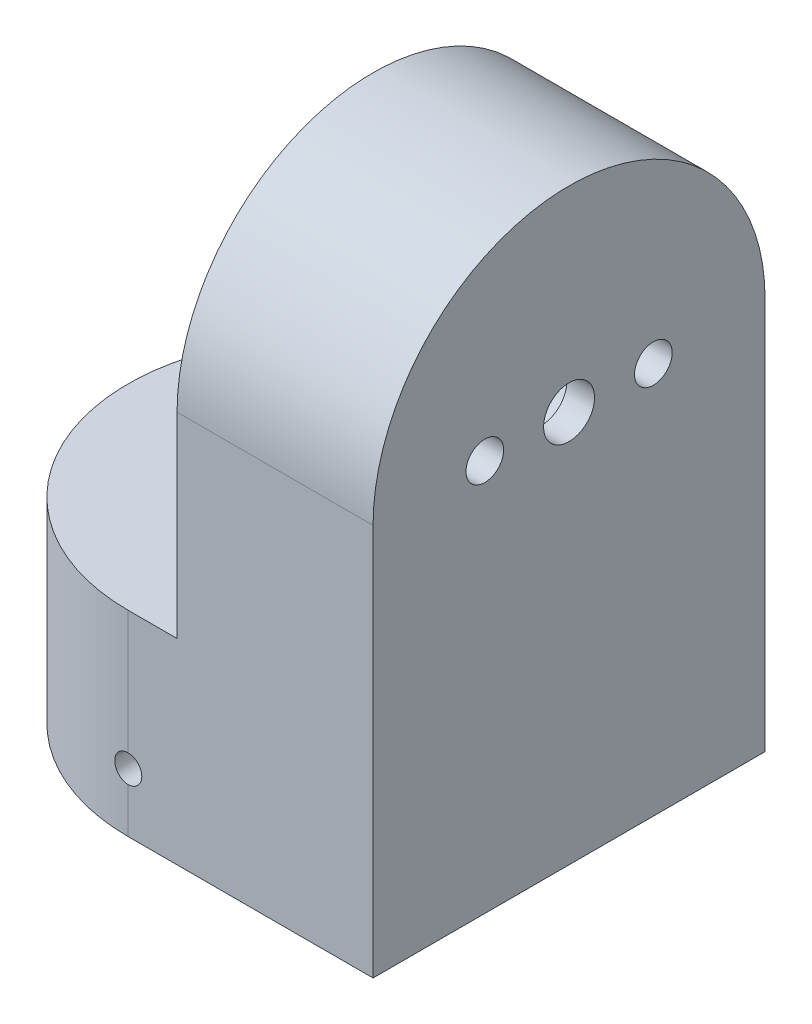
SolidWorks part; units mm, degrees
ref_plane "Front Plane" through (0, 0, 0) normal (0, 0, 1) x (1, 0, 0)
ref_plane "Top Plane" through (0, 0, 0) normal (0, 1, 0) x (1, 0, 0)
ref_plane "Right Plane" through (0, 0, 0) normal (1, 0, 0) x (0, 0, -1)
sketch "Sketch1" plane through (0, 0, 0) normal (0, 1, 0) x (1, 0, 0)
  circle A0 centre (0, 0) radius 12.7
  dimension "D1" = 25.4
extrude "Boss-Extrude1" add sketch "Sketch1" along normal blind 12.7
sketch "Sketch2" plane through (0, 0, 0) normal (0, -1, 0) x (1, 0, 0)
  circle A0 centre (0, 0) radius 1.6256
  dimension "D1" = 3.2512
extrude "Cut-Extrude1" cut sketch "Sketch2" against normal blind 9.525
sketch "Sketch3" plane through (0, 0, 0) normal (0, -1, 0) x (1, 0, 0)
  circle A0 centre (0, 0) radius 9.525
  dimension "D1" = 19.05
extrude "Cut-Extrude2" cut sketch "Sketch3" against normal blind 2.54 contours A0
sketch "Sketch14" plane through (0, 12.7, 0) normal (0, 1, 0) x (1, 0, 0)
  line L0 (0, 12.7) -> (15.875, 12.7)
  line L1 (15.875, 12.7) -> (15.875, -12.7)
  line L2 (15.875, -12.7) -> (0, -12.7)
  circle A0 centre (0, 0) radius 12.7
  circle M3 centre (0, 0) radius 12.7
  dimension "D1" = 25.4
  dimension "D2" = 15.875
extrude "Boss-Extrude6" add sketch "Sketch14" against normal up to surface (12.7 mm away) contours L2 L1 L0 M3 up to face at (0, 0, -9.525)
hole_wizard "#2-56 Tapped Hole1" positions "Sketch6" profile "Sketch5" tap size "#2-56" standard "ANSI Inch"
sketch "Sketch6" plane through (0, 0, 0) normal (0, 0, 1) x (1, 0, 0)
  line L1 (-1.6256, 2.54) -> (1.6256, 2.54) construction
  point P0 (0, 3.81)
  dimension "D1" = 1.27
sketch "Sketch5" plane through (0, 3.81, 0) normal (1, 0, 0) x (0, 1, 0)
  line L0 (0, 0) -> (0, 13.7422)
  line L1 (0, 13.7422) -> (0.889, 13.208)
  line L2 (0.889, 13.208) -> (0.889, 0)
  line L5 (0.889, 0) -> (0, 0)
  line L10 (0, 13.7422) -> (-0.889, 13.208) construction
  line L11 (0, -6.35) -> (0, 107.95) construction
  dimension "Tap Drill Dia." = 1.778
  dimension "Tap Drill Depth" = 13.208
  dimension "Drill Angle" = 118
sketch "Sketch15" plane through (15.875, 0, 0) normal (1, 0, 0) x (0, 0, -1)
  line L1 (12.7, 12.7) -> (-12.7, 12.7) construction
  line L2 (-12.7, 25.4) -> (-12.7, 12.7)
  line L3 (-12.7, 12.7) -> (12.7, 12.7)
  line L4 (12.7, 12.7) -> (12.7, 25.4)
  circle A0 centre (0, 25.4) radius 12.7
  line M4 (12.7, 12.7) -> (-12.7, 12.7)
  dimension "D1" = 25.4
  dimension "D2" = 12.7
  dimension "D3" = 0
extrude "Boss-Extrude8" add sketch "Sketch15" against normal blind 12.7 contours A0 | A0 L2 L3 | A0 L4 M4
sketch "Sketch17" plane through (3.175, 0, 0) normal (-1, 0, 0) x (0, 0, 1)
  line L0 (-12.7, 25.4) -> (12.7, 25.4) construction
  line L1 (0, 38.1) -> (0, 12.7) construction
  line L2 (-12.7, 12.7) -> (12.7, 12.7) construction
  arc A0 (12.7, 25.4) -> (-12.7, 25.4) centre (0, 25.4) ccw construction
  circle A1 centre (0, 25.4) radius 1.651
  dimension "D1" = 3.302
extrude "Cut-Extrude4" cut sketch "Sketch17" against normal up to surface (12.7 mm away) up to face at (15.875, 15.875, 0)
sketch "Sketch18" plane through (3.175, 0, 0) normal (-1, 0, 0) x (0, 0, 1)
  circle A0 centre (0, 25.4) radius 3.81
  dimension "D1" = 7.62
extrude "Cut-Extrude5" cut sketch "Sketch18" against normal offset from surface (10.9028 mm away) 1.7972 up to face at (15.875, 25.4, 1.651)
sketch "Sketch19" plane through (3.175, 0, 0) normal (-1, 0, 0) x (0, 0, 1)
  circle A0 centre (0, 25.4) radius 8.255
  dimension "D1" = 16.51
extrude "Cut-Extrude6" cut sketch "Sketch19" against normal offset from surface (8.3628 mm away) 4.3372 up to face at (15.875, 25.4, 1.651)
sketch "Sketch20" plane through (3.175, 0, 0) normal (-1, 0, 0) x (0, 0, 1)
  circle A0 centre (0, 25.4) radius 9.525
  dimension "D1" = 19.05
extrude "Cut-Extrude7" cut sketch "Sketch20" against normal offset from surface (5.1878 mm away) 7.5122 up to face at (15.875, 25.4, 1.651)
sketch "Sketch21" plane through (11.5378, 0, 0) normal (-1, 0, 0) x (0, 0, 1)
  line L0 (8.255, 25.4) -> (-8.255, 25.4) construction
  circle A0 centre (0, 25.4) radius 8.255 construction
  circle A1 centre (5.46, 25.4) radius 1.2192
  circle A2 centre (-5.46, 25.4) radius 1.2192
  circle A3 centre (0, 25.4) radius 1.651 construction
  dimension "D1" = 2.4384
  dimension "D2" = 2.4384
  dimension "D3" = 10.92
  dimension "D4" = 5.46
extrude "Cut-Extrude8" cut sketch "Sketch21" against normal up to surface (4.3372 mm away) up to face at (15.875, 25.4, 1.651)
